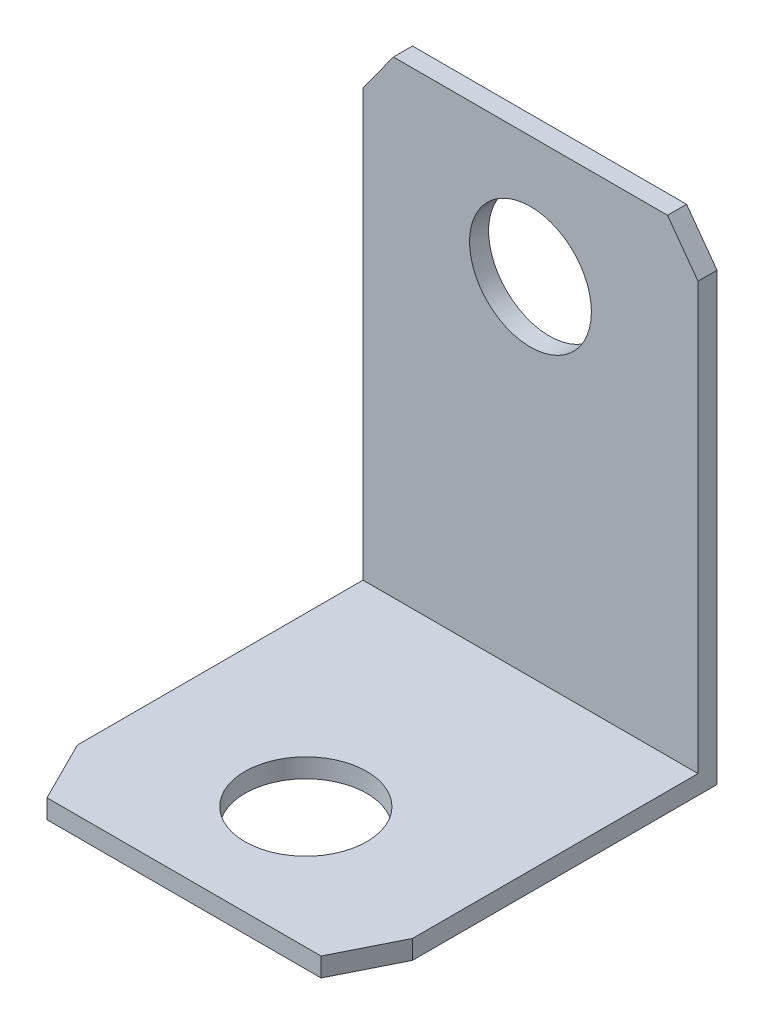
SolidWorks part; units mm, degrees
ref_plane "Front Plane" through (0, 0, 0) normal (0, 0, 1) x (1, 0, 0)
ref_plane "Top Plane" through (0, 0, 0) normal (0, 1, 0) x (1, 0, 0)
ref_plane "Right Plane" through (0, 0, 0) normal (1, 0, 0) x (0, 0, -1)
sketch "Sketch1" plane through (0, 0, 0) normal (0, 1, 0) x (1, 0, 0)
  line L0 (0, 0) -> (34.925, 0)
  line L1 (34.925, 0) -> (34.925, -31.75)
  line L2 (34.925, -31.75) -> (31.75, -38.1)
  line L3 (31.75, -38.1) -> (3.175, -38.1)
  line L4 (3.175, -38.1) -> (0, -31.75)
  line L5 (0, -31.75) -> (0, 0)
  circle A0 centre (17.4625, -25.4) radius 6.35
  point P3 (17.4625, 0)
  point P8 (0, 0)
  point P11 (0, 0)
  dimension "D5" = 12.7
  dimension "D1" = 38.1
  dimension "D2" = 34.925
  dimension "D3" = 28.575
  dimension "D4" = 31.75
  dimension "D6" = 12.7
extrude "Boss-Extrude1" add sketch "Sketch1" along normal blind 1.9844
sketch "Sketch2" plane through (0, 0, 0) normal (0, 0, 1) x (1, 0, 0)
  line L0 (0, 1.9844) -> (0, 46.4344)
  line L1 (0, 46.4344) -> (3.175, 50.8)
  line L2 (3.175, 50.8) -> (31.75, 50.8)
  line L3 (31.75, 50.8) -> (34.925, 46.4344)
  line L4 (34.925, 46.4344) -> (34.925, 1.9844)
  line L5 (34.925, 0) -> (0, 0) construction
  line L10 (0, 0) -> (34.925, 0)
  line L11 (0, 1.9844) -> (0, 0)
  line L12 (34.925, 1.9844) -> (0, 1.9844)
  line L13 (34.925, 0) -> (34.925, 1.9844)
  line L16 (34.925, 1.9844) -> (0, 1.9844)
  circle A0 centre (17.4625, 38.1) radius 6.35
  point P4 (17.4625, 50.8)
  dimension "D5" = 12.7
  dimension "D1" = 50.8
  dimension "D2" = 44.45
  dimension "D3" = 28.575
  dimension "D6" = 12.7
  dimension "D4" = 0
extrude "Boss-Extrude2" add sketch "Sketch2" along normal blind 1.9844
